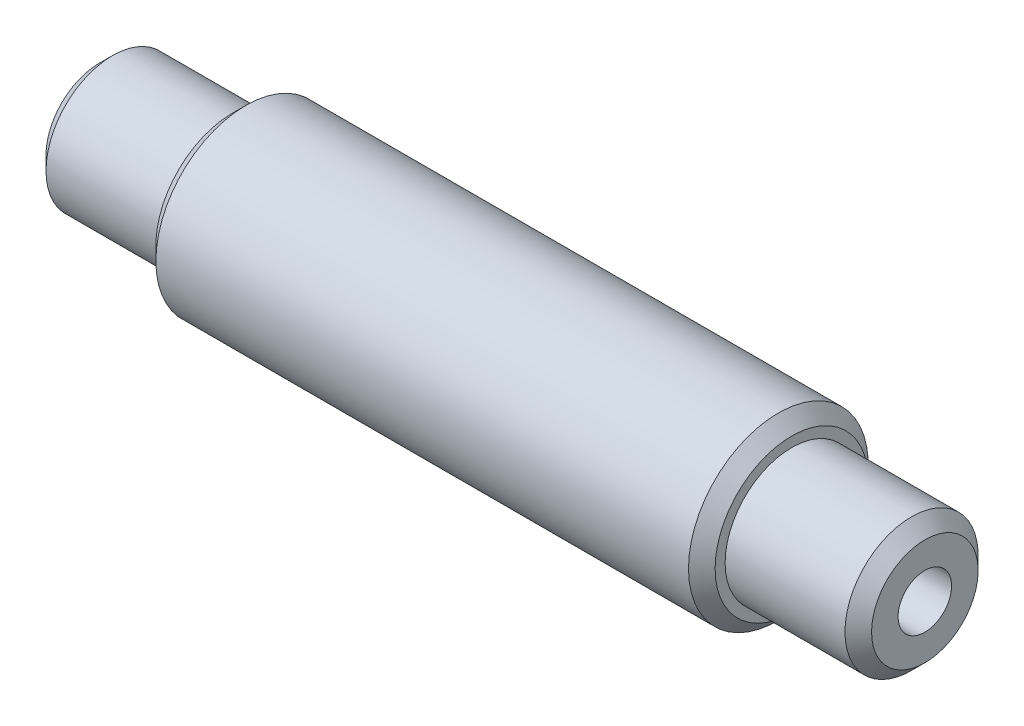
SolidWorks part; units mm, degrees
ref_plane "Front Plane" through (0, 0, 0) normal (0, 0, 1) x (1, 0, 0)
ref_plane "Top Plane" through (0, 0, 0) normal (0, 1, 0) x (1, 0, 0)
ref_plane "Right Plane" through (0, 0, 0) normal (1, 0, 0) x (0, 0, -1)
sketch "Sketch1" plane through (0, 0, 0) normal (0, 0, 1) x (1, 0, 0)
  line L0 (-113.5988, 0) -> (113.5988, 0) construction
  line L1 (0, -16.882) -> (0, 16.882) construction
  line L2 (-39.37, 0) -> (-39.37, 6.35)
  line L3 (-39.37, 6.35) -> (-26.67, 6.35)
  line L4 (-26.67, 6.35) -> (-26.67, 8.5725)
  line L5 (-26.67, 8.5725) -> (26.67, 8.5725)
  line L6 (26.67, 8.5725) -> (26.67, 6.35)
  line L7 (26.67, 6.35) -> (39.37, 6.35)
  line L8 (39.37, 6.35) -> (39.37, 0)
  line L9 (-39.37, 0) -> (39.37, 0)
  point P7 (26.67, 7.4613)
  dimension "D1" = 17.145
  dimension "D2" = 12.7
  dimension "D3" = 78.74
  dimension "D4" = 53.34
revolve "Revolve1" add sketch "Sketch1" angle 360 about L0
chamfer "Chamfer1" distance 1.27 angle 45 4 edges at (-39.37, 0, 6.35) (39.37, 0, 6.35) (26.67, 0, 8.5725) (-26.67, 0, 8.5725)
hole_wizard "1/4-20 Tapped Hole1" positions "Sketch2" profile "Sketch3" tap size "1/4-20" standard "ANSI Inch"
sketch "Sketch2" plane through (39.37, 0, 0) normal (1, 0, 0) x (0, 0, -1)
  point P0 (0, 0)
sketch "Sketch3" plane through (39.37, 0, 0) normal (0, 1, 0) x (0, 0, -1)
  line L0 (0, 0) -> (0, 26.9338)
  line L1 (0, 26.9338) -> (2.5527, 25.4)
  line L2 (2.5527, 25.4) -> (2.5527, 0)
  line L5 (2.5527, 0) -> (0, 0)
  line L10 (0, 26.9338) -> (-2.5527, 25.4) construction
  line L11 (0, -6.35) -> (0, 107.95) construction
  dimension "Tap Drill Dia." = 5.1054
  dimension "Tap Drill Depth" = 25.4
  dimension "Drill Angle" = 118
cosmetic thread "Hole Thread1" parameters "D1"=19.05, "D2"=6.35
hole_wizard "1/4-20 Tapped Hole2" positions "Sketch4" profile "Sketch5" tap size "1/4-20" standard "ANSI Inch"
sketch "Sketch4" plane through (-39.37, 0, 0) normal (-1, 0, 0) x (0, 0, 1)
  point P0 (0, 0)
sketch "Sketch5" plane through (-39.37, 0, 0) normal (0, 1, 0) x (0, 0, 1)
  line L0 (0, 0) -> (0, 26.9338)
  line L1 (0, 26.9338) -> (2.5527, 25.4)
  line L2 (2.5527, 25.4) -> (2.5527, 0)
  line L5 (2.5527, 0) -> (0, 0)
  line L10 (0, 26.9338) -> (-2.5527, 25.4) construction
  line L11 (0, -6.35) -> (0, 107.95) construction
  dimension "Tap Drill Dia." = 5.1054
  dimension "Tap Drill Depth" = 25.4
  dimension "Drill Angle" = 118
cosmetic thread "Hole Thread2" parameters "D1"=19.05, "D2"=6.35
